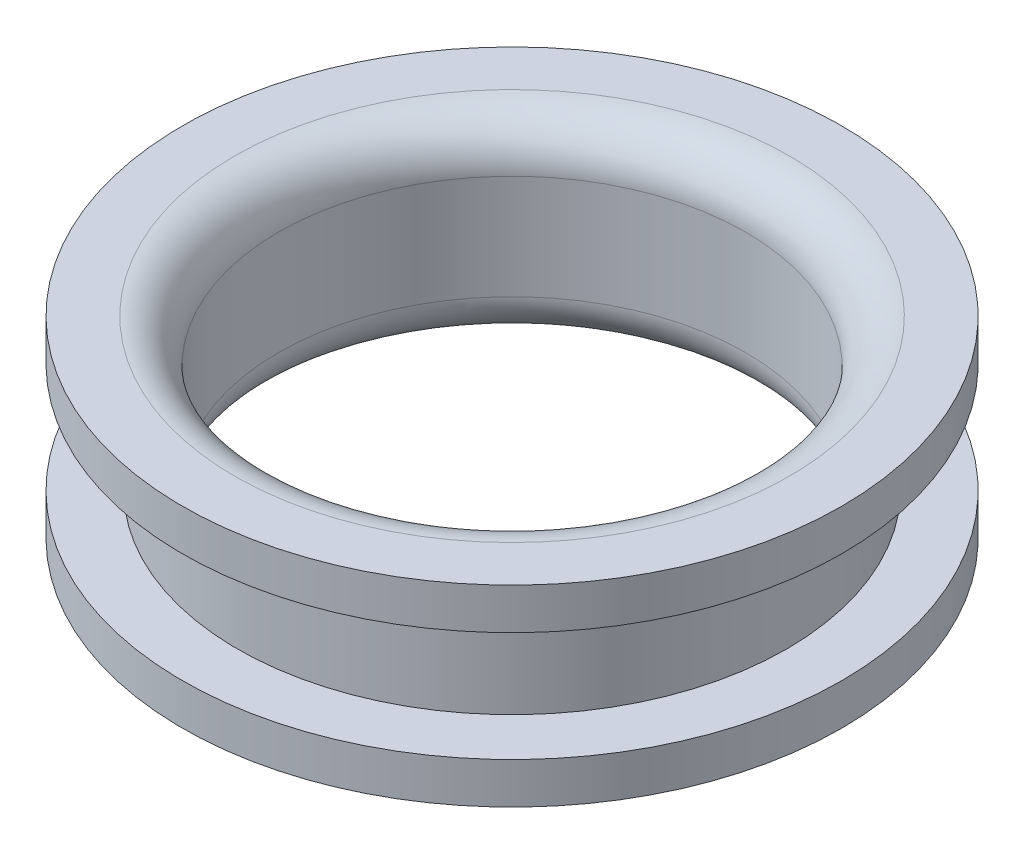
SolidWorks part; units mm, degrees
material "1.0060 (E335)"
ref_plane "Front Plane" through (0, 0, 0) normal (0, 0, 1) x (1, 0, 0)
ref_plane "Top Plane" through (0, 0, 0) normal (0, 1, 0) x (1, 0, 0)
ref_plane "Right Plane" through (0, 0, 0) normal (1, 0, 0) x (0, 0, -1)
sketch "Sketch1" plane through (0, 0, 0) normal (0, 0, 1) x (1, 0, 0)
  line L0 (0, -1019.4497) -> (0, 49953.0371) construction
  line L1 (60, 17.5) -> (42.5, 17.5)
  line L2 (42.5, 17.5) -> (42.5, -17.5)
  line L3 (42.5, -17.5) -> (60, -17.5)
  line L4 (60, -17.5) -> (60, -10)
  line L5 (60, -10) -> (50, -10)
  line L6 (50, -10) -> (50, 10)
  line L7 (50, 10) -> (60, 10)
  line L8 (60, 10) -> (60, 17.5)
  point P1 (42.5, 0)
  point P9 (50, 0)
  dimension "D1" = 7.5
  dimension "D2" = 85
  dimension "D3" = 35
  dimension "D4" = 20
  dimension "D5" = 120
revolve "Revolve1" add sketch "Sketch1" angle 360 about L0
fillet "Fillet1" radius 8 2 edges at (42.5, 17.5, 0) (42.5, -17.5, 0)
